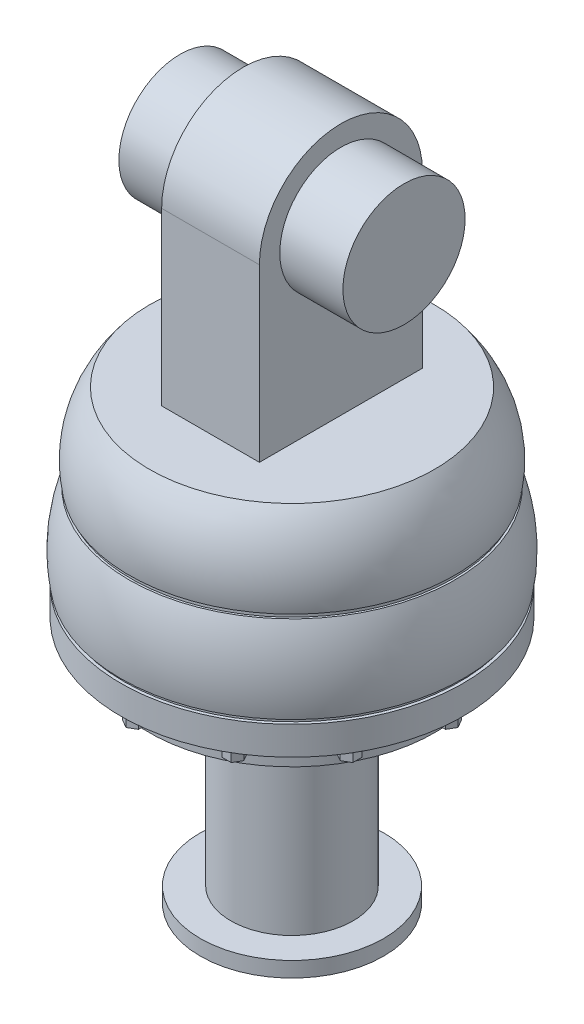
SolidWorks part; units mm, degrees
ref_plane "Front Plane" through (0, 0, 0) normal (0, 0, 1) x (1, 0, 0)
ref_plane "Top Plane" through (0, 0, 0) normal (0, 1, 0) x (1, 0, 0)
ref_plane "Right Plane" through (0, 0, 0) normal (1, 0, 0) x (0, 0, -1)
sketch "Sketch1" plane through (0, 0, 0) normal (0, 0, 1) x (1, 0, 0)
  line L0 (0, 0) -> (-35, 0)
  line L1 (0, 0) -> (0, -20)
  line L2 (0, -20) -> (-40, -20)
  arc A0 (-35, 0) -> (-40, -20) centre (-15.404, -15.524) ccw
  dimension "D4" = 25
  dimension "D1" = 35
  dimension "D2" = 20
  dimension "D3" = 40
revolve "Revolve1" add sketch "Sketch1" angle 360 about L1
sketch "Sketch2" plane through (0, -20, 0) normal (0, -1, 0) x (1, 0, 0)
  circle A0 centre (0, 0) radius 39.5
  dimension "D1" = 79
extrude "Boss-Extrude1" add sketch "Sketch2" along normal blind 1
sketch "Sketch3" plane through (0, 0, 0) normal (1, 0, 0) x (0, 0, -1)
  line L0 (0, -21) -> (-40, -21)
  line L1 (-39.5, -21) -> (39.5, -21) construction
  line L2 (0, -21) -> (0, -41)
  line L3 (0, -41) -> (-42, -41)
  arc A0 (-42, -41) -> (-40, -21) centre (-5.5677, -34.5432) cw
  dimension "D4" = 37
  dimension "D1" = 40
  dimension "D2" = 20
  dimension "D3" = 42
revolve "Revolve2" add sketch "Sketch3" angle 360 about L2
sketch "Sketch4" plane through (0, -41, 0) normal (0, -1, 0) x (1, 0, 0)
  circle A0 centre (0, 0) radius 41.25
  dimension "D1" = 82.5
extrude "Boss-Extrude2" add sketch "Sketch4" along normal blind 1
sketch "Sketch5" plane through (0, -42, 0) normal (0, -1, 0) x (1, 0, 0)
  circle A0 centre (0, 0) radius 42
  dimension "D1" = 84
extrude "Boss-Extrude3" add sketch "Sketch5" along normal blind 7
sketch "Sketch6" plane through (0, -49, 0) normal (0, -1, 0) x (1, 0, 0)
  circle A0 centre (0, 0) radius 35
  dimension "D1" = 70
extrude "Boss-Extrude4" add sketch "Sketch6" along normal blind 7
sketch "Sketch7" plane through (0, -49, 0) normal (0, -1, 0) x (1, 0, 0)
  line L0 (40.75, 0) -> (40.4486, 0)
  line L1 (39.0476, 0.9486) -> (37.9524, 0.9486)
  line L2 (40.75, 0) -> (39.625, 1.9486)
  line L3 (39.625, 1.9486) -> (37.375, 1.9486)
  line L4 (37.375, 1.9486) -> (36.25, 0)
  line L5 (36.25, 0) -> (37.375, -1.9486)
  line L6 (37.375, -1.9486) -> (39.625, -1.9486)
  line L7 (39.625, -1.9486) -> (40.75, 0)
  line L8 (37.9524, 0.9486) -> (37.4047, 0)
  line L9 (37.4047, 0) -> (37.9524, -0.9486)
  line L10 (37.9524, -0.9486) -> (39.0476, -0.9486)
  line L11 (39.0476, -0.9486) -> (39.5953, 0)
  line L12 (39.5953, 0) -> (39.0476, 0.9486)
  line L13 (36.5514, 0) -> (36.25, 0)
  circle A3 centre (38.5, 0) radius 1.9486 construction
  dimension "D1" = 4.5
  dimension "D2" = 1
extrude "Boss-Extrude7" add sketch "Sketch7" along normal blind 3
pattern_circular "CirPattern2" count 12 over 360 about axis through (0, 0, 0) along (0, 1, 0) of "Boss-Extrude7"
sketch "Sketch8" plane through (0, -56, 0) normal (0, -1, 0) x (1, 0, 0)
  circle A0 centre (0, 0) radius 15
  dimension "D1" = 30
extrude "Boss-Extrude8" add sketch "Sketch8" along normal blind 50
sketch "Sketch9" plane through (0, 0, 0) normal (0, 1, 0) x (1, 0, 0)
  line L1 (-12, -20) -> (12, -20)
  line L2 (-12, -20) -> (-12, 20)
  line L3 (-12, 20) -> (12, 20)
  line L4 (12, -20) -> (12, 20)
  line L5 (-12, -20) -> (12, 20) construction
  line L6 (-12, 20) -> (12, -20) construction
  point P0 (0, 0)
  dimension "D1" = 24
  dimension "D2" = 40
extrude "Boss-Extrude9" add sketch "Sketch9" along normal blind 42
sketch "Sketch10" plane through (-12, 0, 0) normal (-1, 0, 0) x (0, 0, 1)
  line L0 (-20, 42) -> (20, 42) construction
  line L1 (-20, 42) -> (20, 42)
  arc A0 (20, 42) -> (-20, 42) centre (0, 42) ccw
extrude "Boss-Extrude10" add sketch "Sketch10" against normal up to vertex
sketch "Sketch11" plane through (-12, 0, 0) normal (-1, 0, 0) x (0, 0, 1)
  circle A0 centre (0, 42) radius 15
  dimension "D1" = 30
extrude "Boss-Extrude11" add sketch "Sketch11" along normal blind 15.5
sketch "Sketch12" plane through (12, 0, 0) normal (1, 0, 0) x (0, 0, -1)
  circle A0 centre (0, 42) radius 15
  dimension "D1" = 30
extrude "Boss-Extrude12" add sketch "Sketch12" along normal blind 15.5
sketch "Sketch13" plane through (0, -106, 0) normal (0, -1, 0) x (1, 0, 0)
  circle A0 centre (0, 0) radius 22.5
extrude "Boss-Extrude13" add sketch "Sketch13" along normal blind 3.75
equation "\"3.75.00mm\"=10"
